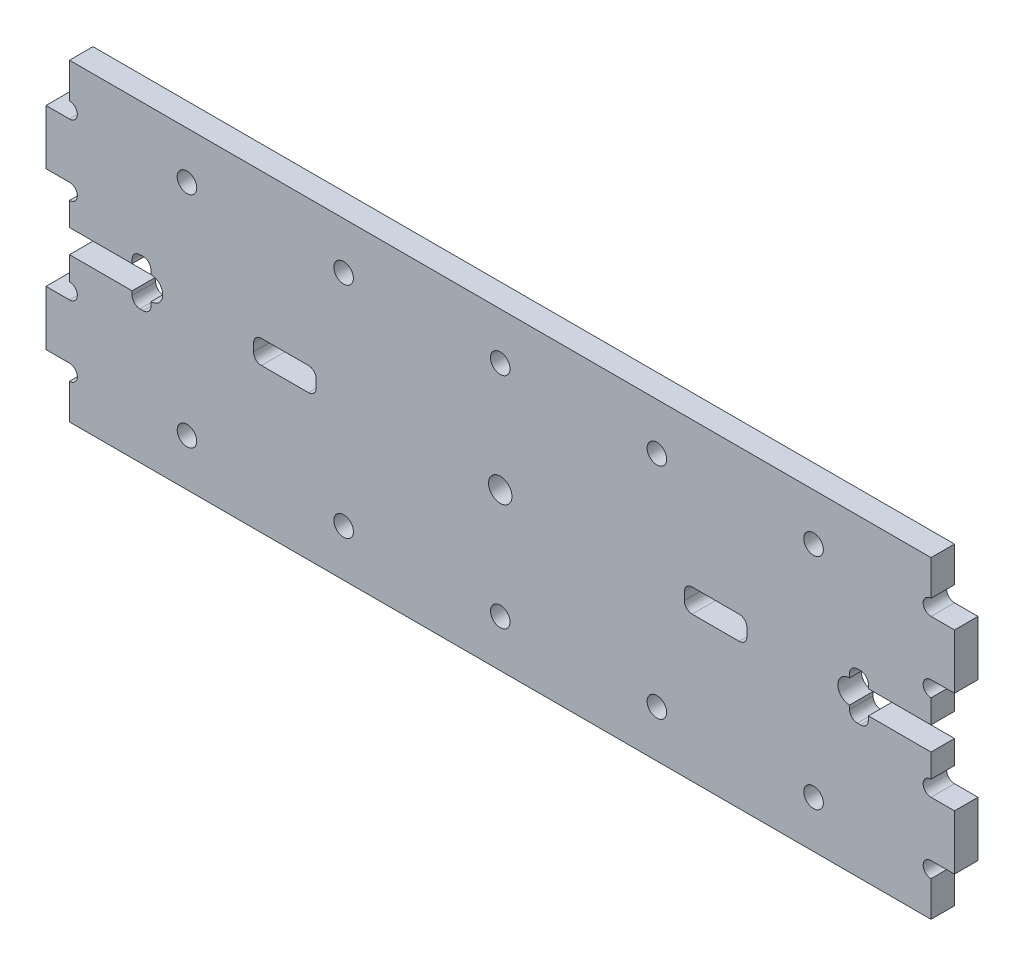
SolidWorks part; units mm, degrees
material "Acrylic (Medium-high impact)"
ref_plane "Front Plane" through (0, 0, 0) normal (0, 0, 1) x (1, 0, 0)
ref_plane "Top Plane" through (0, 0, 0) normal (0, 1, 0) x (1, 0, 0)
ref_plane "Right Plane" through (0, 0, 0) normal (1, 0, 0) x (0, 0, -1)
sketch "Sketch1" plane through (0, 0, 0) normal (0, 0, 1) x (1, 0, 0)
  line L0 (0, 20) -> (0, -20) construction
  line L1 (-55, 20) -> (55, 20)
  line L2 (-55, 20) -> (-55, -20)
  line L3 (-55, -20) -> (55, -20)
  line L4 (55, 20) -> (55, -20)
  line L5 (55, 0) -> (-55, 0) construction
  point P8 (0, 0)
extrude "Boss-Extrude1" add sketch "Sketch1" along normal blind 3
sketch "Sketch2" plane through (0, 0, 3) normal (0, 0, 1) x (1, 0, 0)
  line L0 (-55, 0) -> (55, 0) construction
  line L1 (-55, 20) -> (-55, -20) construction
  line L2 (55, -20) -> (55, 20) construction
  line L3 (55, 0) -> (55, -20) construction
  line L4 (55, 0) -> (55, 20) construction
  line L5 (55, 20) -> (58, 20) construction
  line L6 (58, 20) -> (58, -20) construction
  line L7 (58, -20) -> (55, -20) construction
  line L8 (0, 20) -> (0, -20) construction
  line L9 (55, 20) -> (-55, 20) construction
  line L10 (-55, -20) -> (55, -20) construction
  line L11 (55, -10) -> (58, -10) construction
  line L12 (55, 10) -> (58, 10) construction
  line L13 (58, 10) -> (58, 13.5)
  line L14 (58, 10) -> (58, 6.5)
  line L15 (58, 6.5) -> (55, 6.5)
  line L16 (55, 6.5) -> (55, 13.5)
  line L17 (55, 13.5) -> (58, 13.5)
  line L18 (55, -10) -> (55, -6.5)
  line L19 (55, -6.5) -> (58, -6.5)
  line L20 (58, -6.5) -> (58, -13.5)
  line L21 (58, -13.5) -> (55, -13.5)
  line L22 (55, -13.5) -> (55, -10)
  line L23 (-55, 6.5) -> (-55, 13.5)
  line L24 (-55, -13.5) -> (-55, -10)
  line L25 (-55, -10) -> (-55, -6.5)
  line L26 (-55, 10) -> (-58, 10) construction
  line L27 (-55, -10) -> (-58, -10) construction
  line L28 (-58, -20) -> (-55, -20) construction
  line L29 (-58, 20) -> (-58, -20) construction
  line L30 (-55, 20) -> (-58, 20) construction
  line L31 (-58, -13.5) -> (-55, -13.5)
  line L32 (-58, -6.5) -> (-58, -13.5)
  line L33 (-55, -6.5) -> (-58, -6.5)
  line L34 (-55, 13.5) -> (-58, 13.5)
  line L35 (-58, 6.5) -> (-55, 6.5)
  line L36 (-58, 10) -> (-58, 6.5)
  line L37 (-58, 10) -> (-58, 13.5)
extrude "Boss-Extrude2" add sketch "Sketch2" against normal blind 3
sketch "Sketch3" plane through (0, 0, 3) normal (0, 0, 1) x (1, 0, 0)
  line L0 (-55, 0) -> (55, 0) construction
  line L1 (-55, 6.5) -> (-55, -6.5) construction
  line L2 (55, -6.5) -> (55, 6.5) construction
  line L3 (-55, 13.5) -> (-55, 14.5) construction
  line L4 (-55, 20) -> (-55, 13.5) construction
  line L5 (-55, 14.5) -> (55, 14.5) construction
  line L6 (55, 13.5) -> (55, 20) construction
  line L7 (55, 14.5) -> (55, 5.5) construction
  line L8 (55, 5.5) -> (-55, 5.5) construction
  line L9 (-55, -6.5) -> (-55, -5.5) construction
  line L10 (-55, -5.5) -> (55, -5.5) construction
  line L11 (55, -5.5) -> (55, -14.5) construction
  line L12 (55, -20) -> (55, -13.5) construction
  line L13 (55, -14.5) -> (-55, -14.5) construction
  line L14 (-55, -13.5) -> (-55, -20) construction
  circle A0 centre (0, 0) radius 1.5
  circle A1 centre (-55, 14.5) radius 1
  circle A2 centre (-55, 5.5) radius 1
  circle A3 centre (-55, -5.5) radius 1
  circle A4 centre (-55, -14.5) radius 1
  circle A5 centre (55, 14.5) radius 1
  circle A6 centre (55, 5.5) radius 1
  circle A7 centre (55, -5.5) radius 1
  circle A8 centre (55, -14.5) radius 1
  line M2 (-55, 20) -> (-55, 13.5)
  line M6 (-55, 6.5) -> (-55, -6.5)
  line M10 (-55, -13.5) -> (-55, -20)
  line M12 (55, -20) -> (55, -13.5)
  line M16 (55, -6.5) -> (55, 6.5)
  line M20 (55, 13.5) -> (55, 20)
extrude "Cut-Extrude1" cut sketch "Sketch3" against normal blind 3 contours A4 M10 | A3 M6 | A2 M6 | A1 M2 | A0 | A7 M16 | A8 M12 | A6 M16 | A5 M20
sketch "Sketch4" plane through (0, 0, 3) normal (0, 0, 1) x (1, 0, 0)
  line L0 (-55, 0) -> (55, 0) construction
  line L1 (-55, 4.5) -> (-55, -4.5) construction
  line L2 (55, -4.5) -> (55, 4.5) construction
  line L3 (55, 0) -> (55, -1.5) construction
  line L4 (55, -1.5) -> (-55, -1.5) construction
  line L5 (-55, -1.5) -> (-55, 1.5) construction
  line L6 (-55, 1.5) -> (55, 1.5) construction
  line L7 (55, 1.5) -> (47, 1.5) construction
  line L8 (47, 20) -> (47, -20) construction
  line L9 (55, 20) -> (-55, 20) construction
  line L10 (-55, -20) -> (55, -20) construction
  line L11 (-55, 1.5) -> (-47, 1.5) construction
  line L12 (-47, 20) -> (-47, -20) construction
  line L13 (-47, 20) -> (-44.6, 20) construction
  line L14 (-44.6, 20) -> (-44.6, -20) construction
  line L15 (47, 20) -> (44.6, 20) construction
  line L16 (44.6, 20) -> (44.6, -20) construction
  line L17 (55, 1.5) -> (55, 3) construction
  line L18 (55, 3) -> (-55, 3) construction
  line L19 (-55, 3) -> (-55, -3) construction
  line L20 (-55, -3) -> (55, -3) construction
  line L21 (-44.6, 0) -> (-43.1, 0) construction
  line L22 (44.6, 0) -> (43.1, 0) construction
  line L24 (-55, 1.5) -> (-47, 1.5)
  line L25 (-55, 1.5) -> (-55, -1.5)
  line L26 (-55, -1.5) -> (-47, -1.5)
  line L27 (-47, 1.5) -> (-47, -1.5)
  line L28 (-47, 3) -> (-44.6, 3)
  line L29 (-47, 3) -> (-47, -3)
  line L30 (-47, -3) -> (-44.6, -3)
  line L31 (-44.6, 3) -> (-44.6, -3)
  line L32 (44.6, 3) -> (47, 3)
  line L33 (44.6, 3) -> (44.6, -3)
  line L34 (44.6, -3) -> (47, -3)
  line L35 (47, 3) -> (47, -3)
  line L36 (47, 1.5) -> (55, 1.5)
  line L37 (47, 1.5) -> (47, -1.5)
  line L38 (47, -1.5) -> (55, -1.5)
  line L39 (55, 1.5) -> (55, -1.5)
  arc A0 (44.6, 1.5) -> (44.6, -1.5) centre (44.6, 0) ccw
  arc A1 (-44.6, 1.5) -> (-44.6, -1.5) centre (-44.6, 0) cw
  line M10 (-55, 4.5) -> (-55, -4.5)
  line M24 (55, -4.5) -> (55, 4.5)
extrude "Cut-Extrude2" cut sketch "Sketch4" against normal blind 3 contours L27 L24 L26 M10 | L31 L28 L29 L27 L30 | A1 L31 | L35 L32 L33 L34 | L33 A0 | L35 L38 L36 M24
fillet "Fillet6" radius 1 8 edges at (-44.6, 3, 1.5) (-47, 3, 1.5) (-44.6, -3, 1.5) (-47, -3, 1.5) (47, 3, 1.5) (44.6, 3, 1.5) (47, -3, 1.5) (44.6, -3, 1.5)
sketch "Sketch5" plane through (0, 0, 3) normal (0, 0, 1) x (1, 0, 0)
  line L0 (-55, -1.5) -> (-55, 1.5) construction
  line L1 (55, -1.5) -> (55, 1.5) construction
  line L2 (-55, 0) -> (0, 0) construction
  line L3 (0, 0) -> (55, 0) construction
  line L4 (-27.5, 0) -> (-27.5, 1.5) construction
  line L5 (-27.5, 1.5) -> (-23.5, 1.5) construction
  line L6 (-23.5, 1.5) -> (-23.5, -1.5) construction
  line L7 (-23.5, -1.5) -> (-31.5, -1.5) construction
  line L8 (-31.5, -1.5) -> (-31.5, 1.5) construction
  line L9 (-31.5, 1.5) -> (-27.5, 1.5) construction
  line L10 (27.5, 0) -> (27.5, 1.5) construction
  line L11 (27.5, 1.5) -> (31.5, 1.5) construction
  line L12 (31.5, 1.5) -> (31.5, -1.5) construction
  line L13 (31.5, -1.5) -> (23.5, -1.5) construction
  line L14 (23.5, -1.5) -> (23.5, 1.5) construction
  line L15 (23.5, 1.5) -> (27.5, 1.5) construction
  line L17 (-31.5, 1.5) -> (-23.5, 1.5)
  line L18 (-31.5, 1.5) -> (-31.5, -1.5)
  line L19 (-31.5, -1.5) -> (-23.5, -1.5)
  line L20 (-23.5, 1.5) -> (-23.5, -1.5)
  line L21 (23.5, 1.5) -> (31.5, 1.5)
  line L22 (23.5, 1.5) -> (23.5, -1.5)
  line L23 (23.5, -1.5) -> (31.5, -1.5)
  line L24 (31.5, 1.5) -> (31.5, -1.5)
extrude "Cut-Extrude3" cut sketch "Sketch5" against normal blind 10
fillet "Fillet7" radius 1 8 edges at (-31.5, -1.5, 1.5) (-31.5, 1.5, 1.5) (-23.5, 1.5, 1.5) (23.5, -1.5, 1.5) (23.5, 1.5, 1.5) (31.5, 1.5, 1.5) (31.5, -1.5, 1.5) (-23.5, -1.5, 1.5)
sketch "Sketch6" plane through (0, 0, 3) normal (0, 0, 1) x (1, 0, 0)
  line L0 (0, 0) -> (0, 20) construction
  line L1 (55, 20) -> (-55, 20) construction
  line L2 (0, 20) -> (0, 14) construction
  line L3 (0, 0) -> (0, -20) construction
  line L4 (-55, -20) -> (55, -20) construction
  line L5 (0, -20) -> (0, -14) construction
  circle A0 centre (0, 14) radius 1.25
  circle A1 centre (0, -14) radius 1.25
  circle A2 centre (20, -14) radius 1.25
  circle A3 centre (20, 14) radius 1.25
  circle A4 centre (40, -14) radius 1.25
  circle A5 centre (40, 14) radius 1.25
  circle A6 centre (-20, -14) radius 1.25
  circle A7 centre (-20, 14) radius 1.25
  circle A8 centre (-40, -14) radius 1.25
  circle A9 centre (-40, 14) radius 1.25
  dimension "D1" = 3
  dimension "D2" = 3
extrude "Cut-Extrude4" cut sketch "Sketch6" against normal through all contours A8 | A6 | A1 | A2 | A4 | A5 | A3 | A0 | A7 | A9
